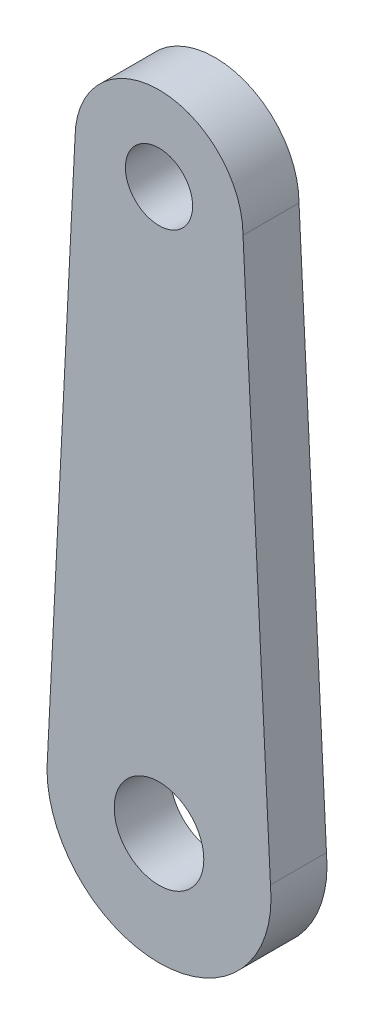
SolidWorks part; units mm, degrees
ref_plane "Front Plane" through (0, 0, 0) normal (0, 0, 1) x (1, 0, 0)
ref_plane "Top Plane" through (0, 0, 0) normal (0, 1, 0) x (1, 0, 0)
ref_plane "Right Plane" through (0, 0, 0) normal (1, 0, 0) x (0, 0, -1)
sketch "Sketch1" plane through (0, 0, 0) normal (0, 0, 1) x (1, 0, 0)
  line L0 (-7.5, 50) -> (-9.9501, 0.9975)
  line L1 (7.5, 50) -> (9.9501, 0.9975)
  arc A0 (-9.9501, 0.9975) -> (9.9501, 0.9975) centre (0, 0) ccw
  arc A1 (7.5, 50) -> (-7.5, 50) centre (0, 50) ccw
  circle A2 centre (0, 0) radius 4
  circle A3 centre (0, 50) radius 3
  dimension "D1" = 20
  dimension "D2" = 15
  dimension "D4" = 8
  dimension "D5" = 6
  dimension "D3" = 50
extrude "Boss-Extrude1" add sketch "Sketch1" along normal blind 5
